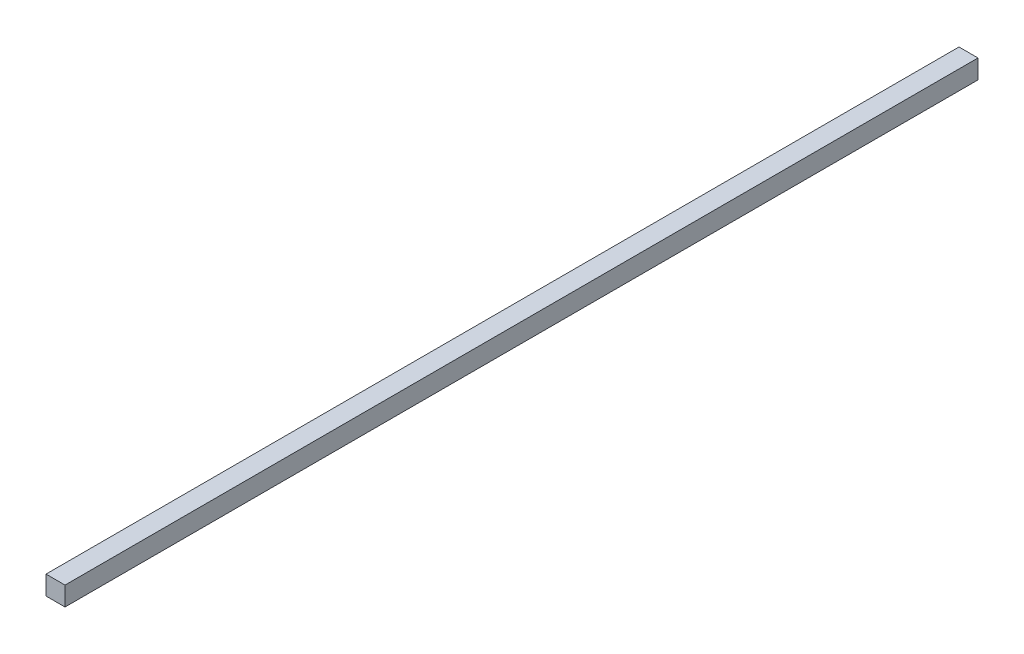
SolidWorks part; units mm, degrees
material "STAINLESS STEEL"
ref_plane "Front Plane" through (0, 0, 0) normal (0, 0, 1) x (1, 0, 0)
ref_plane "Top Plane" through (0, 0, 0) normal (0, 1, 0) x (1, 0, 0)
ref_plane "Right Plane" through (0, 0, 0) normal (1, 0, 0) x (0, 0, -1)
sketch "Sketch1" plane through (0, 0, 0) normal (0, 0, 1) x (1, 0, 0)
  line L1 (-1.5875, 1.5875) -> (1.5875, 1.5875)
  line L2 (-1.5875, 1.5875) -> (-1.5875, -1.5875)
  line L3 (-1.5875, -1.5875) -> (1.5875, -1.5875)
  line L4 (1.5875, 1.5875) -> (1.5875, -1.5875)
  line L5 (-1.5875, 1.5875) -> (1.5875, -1.5875) construction
  line L6 (-1.5875, -1.5875) -> (1.5875, 1.5875) construction
  point P0 (0, 0)
  dimension "D1" = 3.175
extrude "Boss-Extrude1" add sketch "Sketch1" along normal blind 152.4
